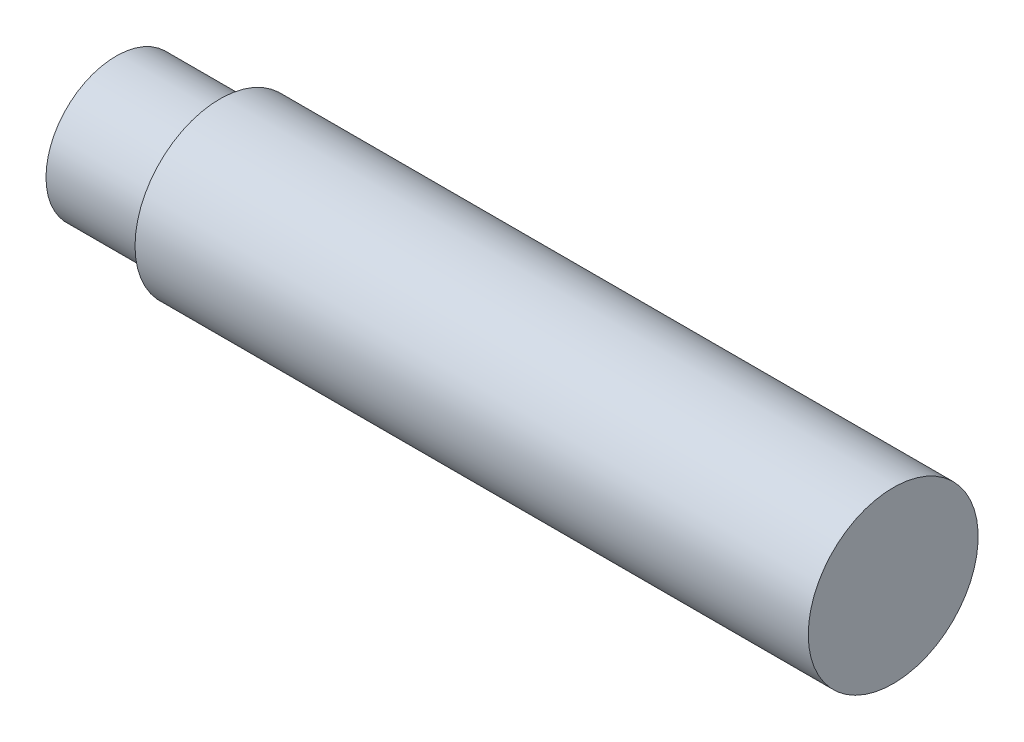
SolidWorks part; units mm, degrees
material "AISI 304"
ref_plane "Front Plane" through (0, 0, 0) normal (0, 0, 1) x (1, 0, 0)
ref_plane "Top Plane" through (0, 0, 0) normal (0, 1, 0) x (1, 0, 0)
ref_plane "Right Plane" through (0, 0, 0) normal (1, 0, 0) x (0, 0, -1)
sketch "Sketch3" plane through (0, 0, 0) normal (0, 0, 1) x (1, 0, 0)
  line L0 (0, 0) -> (50000, 0) construction
  line L1 (0, 0) -> (0, -1.9685)
  line L2 (0, -1.9685) -> (2.921, -1.9685)
  line L3 (2.921, -1.9685) -> (2.921, -2.3876)
  line L4 (2.921, -2.3876) -> (21.844, -2.3876)
  line L5 (21.844, -2.3876) -> (21.844, 0)
  line L6 (0, 0) -> (21.844, 0)
  dimension "D1" = 3.937
  dimension "D2" = 4.7752
  dimension "D3" = 21.844
  dimension "D4" = 2.921
revolve "Revolve1" add sketch "Sketch3" angle 360 about L0
hole_wizard "#4-40 Tapped Hole1" positions "Sketch5" profile "Sketch4" tap size "#4-40" standard "ANSI Inch"
sketch "Sketch5" plane through (0, 0, 0) normal (-1, 0, 0) x (0, 0, 1)
  point P0 (0, 0)
sketch "Sketch4" plane through (0, 0, 0) normal (0, 1, 0) x (0, 0, 1)
  line L0 (0, 0) -> (0, 11.0932)
  line L1 (0, 11.0932) -> (1.1303, 10.414)
  line L2 (1.1303, 10.414) -> (1.1303, 0.7919)
  line L3 (1.1303, 0.7919) -> (1.5875, 0)
  line L5 (1.5875, 0) -> (0, 0)
  line L6 (-1.1303, 0.7919) -> (-1.5875, 0) construction
  line L10 (0, 11.0932) -> (-1.1303, 10.414) construction
  line L11 (0, -6.35) -> (0, 107.95) construction
  dimension "Tap Drill Dia." = 2.2606
  dimension "Tap Drill Depth" = 10.414
  dimension "Near C'Sink Dia." = 3.175
  dimension "Near C'Sink Angle" = 60
  dimension "Drill Angle" = 118
cosmetic thread "Hole Thread3" parameters "D1"=8.382, "D2"=2.8448
